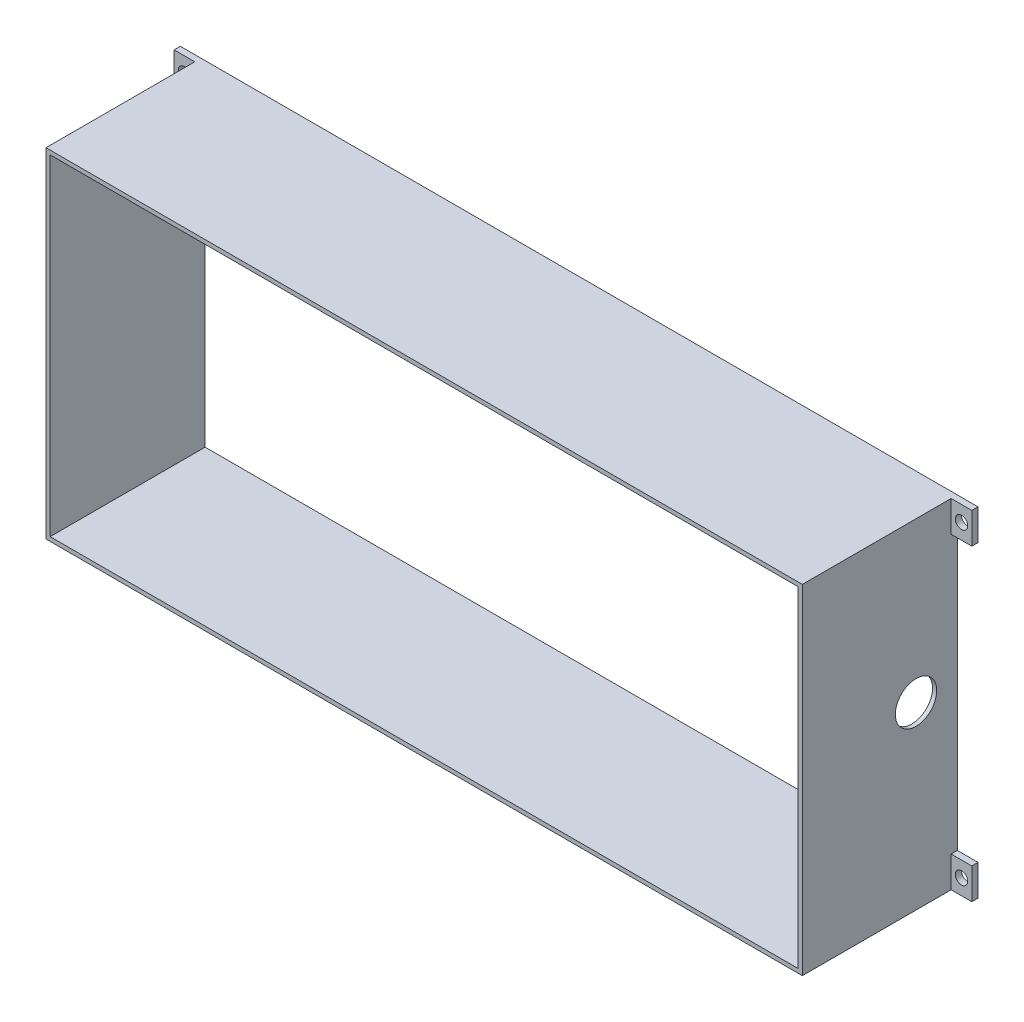
SolidWorks part; units mm, degrees
ref_plane "前基準面" through (0, 0, 0) normal (0, 0, 1) x (1, 0, 0)
ref_plane "上基準面" through (0, 0, 0) normal (0, 1, 0) x (1, 0, 0)
ref_plane "右基準面" through (0, 0, 0) normal (1, 0, 0) x (0, 0, -1)
sketch "草圖1" plane through (0, 0, 0) normal (0, 0, 1) x (1, 0, 0)
  line L1 (-183, 82) -> (183, 82)
  line L2 (-183, 82) -> (-183, -82)
  line L3 (-183, -82) -> (183, -82)
  line L4 (183, 82) -> (183, -82)
  line L5 (-183, 82) -> (183, -82) construction
  line L6 (-183, -82) -> (183, 82) construction
  line L7 (-181, 80) -> (181, 80)
  line L8 (-181, 80) -> (-181, -80)
  line L9 (-181, -80) -> (181, -80)
  line L10 (181, 80) -> (181, -80)
  line L11 (-181, 80) -> (181, -80) construction
  line L12 (-181, -80) -> (181, 80) construction
  point P0 (0, 0)
  point P6 (0, 0)
  dimension "D1" = 366
  dimension "D2" = 164
  dimension "D3" = 160
  dimension "D4" = 362
extrude "填料-伸長1" add sketch "草圖1" along normal blind 75
sketch "草圖2" plane through (183, 0, 0) normal (1, 0, 0) x (0, 0, -1)
  line L1 (0, 82) -> (-3, 82)
  line L2 (0, 82) -> (0, 67)
  line L3 (0, 67) -> (-3, 67)
  line L4 (-3, 82) -> (-3, 67)
  line L5 (0, -82) -> (-3, -82)
  line L6 (0, -82) -> (0, -67)
  line L7 (0, -67) -> (-3, -67)
  line L8 (-3, -82) -> (-3, -67)
  dimension "D1" = 3
  dimension "D2" = 15
  dimension "D3" = 3
  dimension "D4" = 15
extrude "填料-伸長2" add sketch "草圖2" along normal blind 10
sketch "草圖3" plane through (0, 0, 3) normal (0, 0, 1) x (1, 0, 0)
  line L0 (193, 82) -> (183, 82) construction
  line L1 (193, -67) -> (183, -67) construction
  line L2 (183, 82) -> (183, 67) construction
  line L5 (183, -82) -> (183, 82) construction
  circle A0 centre (188, 74.5) radius 3
  circle A2 centre (188, -74.5) radius 3
  dimension "D1" = 6
  dimension "D6" = 6
  dimension "D2" = 7.5
  dimension "D3" = 7.5
  dimension "D4" = 5
  dimension "D5" = 5
mirror "鏡射1" about plane through (0, 0, 0) normal (1, 0, 0) of "填料-伸長2"
extrude "除料-伸長1" cut sketch "草圖3" against normal blind 10
mirror "鏡射3" about plane through (0, 0, 0) normal (1, 0, 0) of "除料-伸長1"
sketch "草圖4" plane through (183, 0, 0) normal (1, 0, 0) x (0, 0, -1)
  line L0 (0, -67) -> (0, 67) construction
  line L1 (-75, 82) -> (-3, 82) construction
  circle A0 centre (-20, 5) radius 10
  dimension "D2" = 20
  dimension "D1" = 20
  dimension "D3" = 77
extrude "除料-伸長2" cut sketch "草圖4" against normal blind 10
